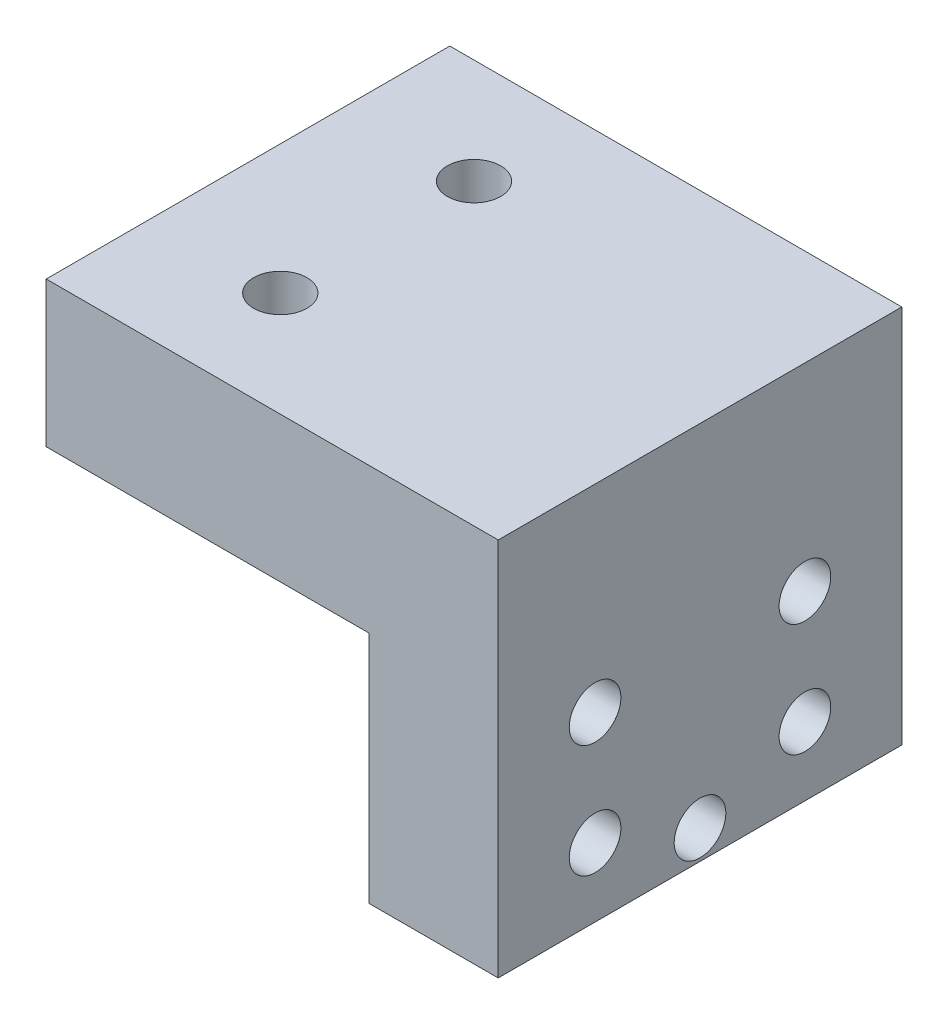
SolidWorks part; units mm, degrees
ref_plane "前视基准面" through (0, 0, 0) normal (0, 0, 1) x (1, 0, 0)
ref_plane "上视基准面" through (0, 0, 0) normal (0, 1, 0) x (1, 0, 0)
ref_plane "右视基准面" through (0, 0, 0) normal (1, 0, 0) x (0, 0, -1)
sketch "草图1" plane through (0, 0, 0) normal (0, 0, 1) x (1, 0, 0)
  line L0 (0, 0) -> (0, 23.5)
  line L1 (0, 23.5) -> (-28, 23.5)
  line L2 (-28, 23.5) -> (-28, 14.5)
  line L3 (-28, 14.5) -> (-8, 14.5)
  line L4 (-8, 14.5) -> (-8, 0)
  line L5 (-8, 0) -> (0, 0)
  dimension "D1" = 8
  dimension "D2" = 23.5
  dimension "D3" = 20
  dimension "D4" = 9
extrude "凸台-拉伸1" add sketch "草图1" along normal blind 25
sketch "草图2" plane through (0, 23.5, 0) normal (0, 1, 0) x (1, 0, 0)
  line L0 (-28, -25) -> (-28, 0) construction
  line L5 (-20, -12.5) -> (-20, 0) construction
  line L6 (0, 0) -> (-28, 0) construction
  line L7 (-20, -12.5) -> (-20, -25) construction
  line L8 (0, -25) -> (-28, -25) construction
  circle A4 centre (-20, -6.5) radius 1.65
  circle A5 centre (-20, -18.5) radius 1.65
  point P0 (-20, -12.5)
  point P7 (-28, -12.5)
  dimension "D4" = 3.3
  dimension "D2" = 3.3
  dimension "D1" = 6
  dimension "D3" = 8
  dimension "D5" = 6
extrude "切除-拉伸1" cut sketch "草图2" against normal blind 33
sketch "草图3" plane through (-8, 0, 0) normal (-1, 0, 0) x (0, 0, 1)
  line L0 (6, 1.8) -> (6, 11.25) construction
  line L1 (6, 11.25) -> (19, 11.25) construction
  line L2 (19, 11.25) -> (19, 1.8) construction
  line L3 (19, 1.8) -> (12.5, 1.8) construction
  line L4 (12.5, 1.8) -> (6, 1.8) construction
  line L5 (25, 0) -> (0, 0) construction
  line L6 (6, 4.25) -> (19, 4.25) construction
  circle A1 centre (6, 11.25) radius 1.6
  circle A3 centre (19, 11.25) radius 1.6
  circle A5 centre (12.5, 1.8) radius 1.6
  circle A6 centre (6, 4.25) radius 1.6
  circle A7 centre (19, 4.25) radius 1.6
  point P10 (12.5, 0)
  point P14 (12.5, 1.8)
  dimension "D2" = 3.2
  dimension "D1" = 13
  dimension "D3" = 1.8
  dimension "D4" = 7
  dimension "D5" = 4.25
extrude "切除-拉伸2" cut sketch "草图3" against normal blind 33
sketch "草图4" plane through (0, 0, 0) normal (0, -1, 0) x (1, 0, 0)
  line L0 (-8, 25) -> (-8, 0) construction
  line L1 (0, 25) -> (0, 0) construction
  line L2 (-8, 14.7249) -> (-8, 10.2751)
  line L3 (-8, 25) -> (-8, 0) construction
  arc A0 (-8, 10.2751) -> (-8, 14.7249) centre (-5.7, 12.5) ccw
  point P4 (0, 12.5)
  point P8 (-5.7, 12.5)
  dimension "D2" = 6.4
  dimension "D1" = 2.3
extrude "切除-拉伸3" cut sketch "草图4" against normal up to surface (14.5 mm away) up to face at (-20, 14.5, 8.15)
